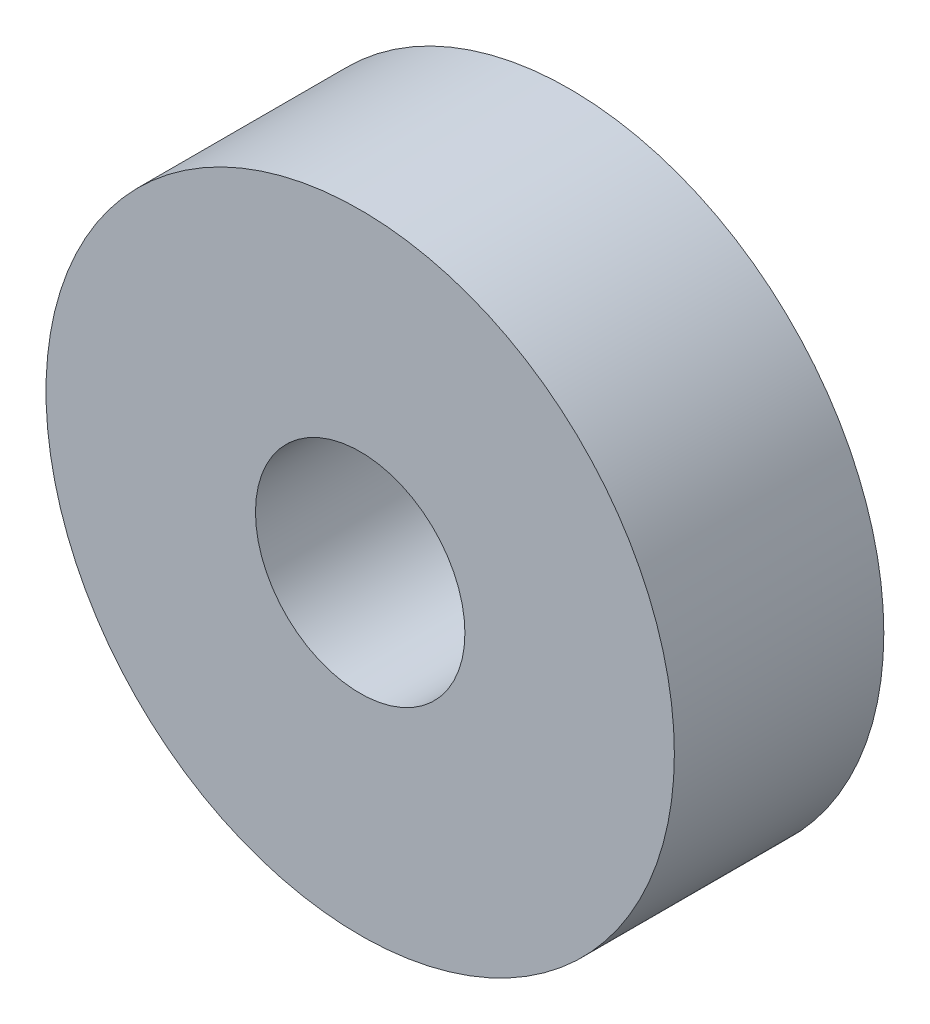
SolidWorks part; units mm, degrees
ref_plane "Front Plane" through (0, 0, 0) normal (0, 0, 1) x (1, 0, 0)
ref_plane "Top Plane" through (0, 0, 0) normal (0, 1, 0) x (1, 0, 0)
ref_plane "Right Plane" through (0, 0, 0) normal (1, 0, 0) x (0, 0, -1)
sketch "Sketch1" plane through (0, 0, 0) normal (0, 0, 1) x (1, 0, 0)
  circle A0 centre (0, 0) radius 2
  circle A1 centre (0, 0) radius 6
  dimension "D1" = 4
  dimension "D2" = 12
extrude "Boss-Extrude1" add sketch "Sketch1" along normal mid plane 4
